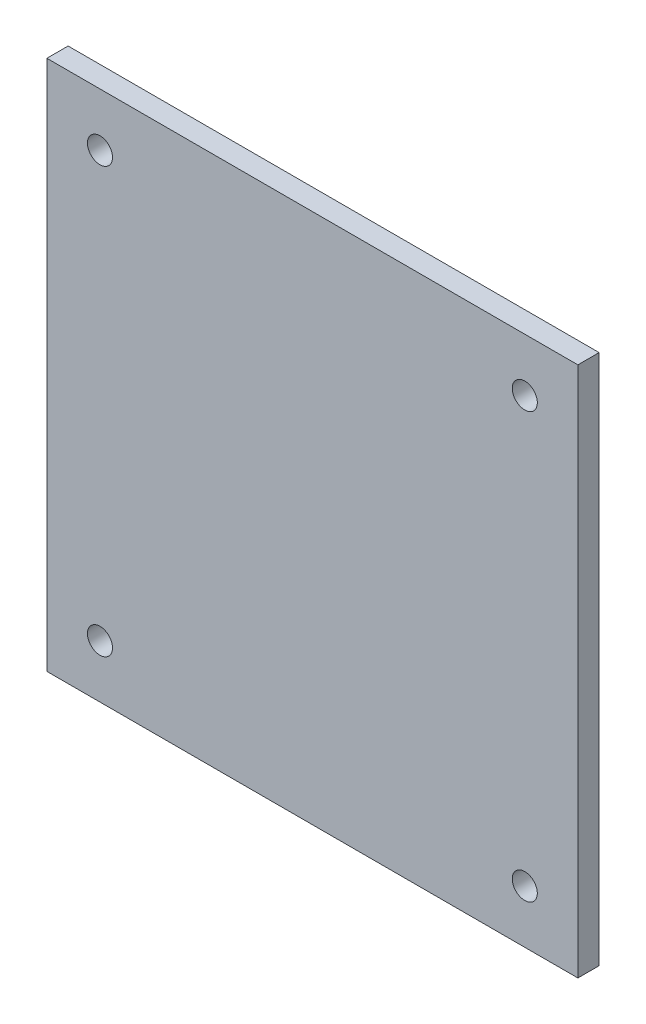
SolidWorks part; units mm, degrees
ref_plane "Front Plane" through (0, 0, 0) normal (0, 0, 1) x (1, 0, 0)
ref_plane "Top Plane" through (0, 0, 0) normal (0, 1, 0) x (1, 0, 0)
ref_plane "Right Plane" through (0, 0, 0) normal (1, 0, 0) x (0, 0, -1)
sketch "Sketch1" plane through (0, 0, 0) normal (0, 0, 1) x (1, 0, 0)
  line L1 (0, 0) -> (63.5, 0)
  line L2 (0, 0) -> (0, 63.5)
  line L3 (0, 63.5) -> (63.5, 63.5)
  line L4 (63.5, 0) -> (63.5, 63.5)
  dimension "D1" = 63.5
extrude "Boss-Extrude1" add sketch "Sketch1" along normal blind 2.54
sketch "Sketch2" plane through (0, 0, 2.54) normal (0, 0, 1) x (1, 0, 0)
  line L0 (0, 63.5) -> (0, 0) construction
  line L1 (63.5, 63.5) -> (0, 63.5) construction
  circle A0 centre (6.35, 57.15) radius 1.5
  dimension "D3" = 3
  dimension "D1" = 6.35
  dimension "D2" = 6.35
extrude "Cut-Extrude1" cut sketch "Sketch2" against normal blind 2.54
pattern_linear "LPattern1" count 2 spacing 50.8 along (1, 0, 0) count 2 spacing 50.8 along (0, -1, 0) of "Cut-Extrude1"
